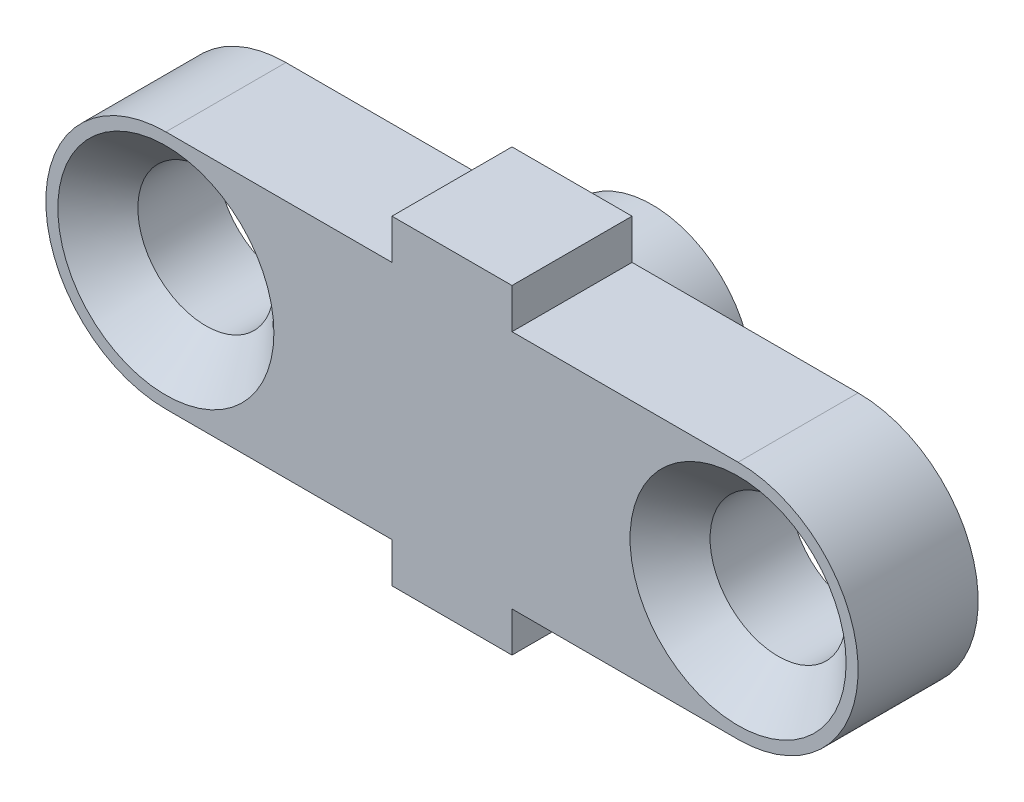
SolidWorks part; units mm, degrees
ref_plane "Top Plane" through (0, 0, 0) normal (0, 0, 1) x (1, 0, 0)
ref_plane "Right Plane" through (0, 0, 0) normal (0, 1, 0) x (1, 0, 0)
ref_plane "Front Plane" through (0, 0, 0) normal (1, 0, 0) x (0, 0, -1)
sketch "Sketch1" plane through (0, 0, 0) normal (0, 0, 1) x (1, 0, 0)
  line L0 (-7.15, 0) -> (7.15, 0) construction
  line L1 (-7.15, 3) -> (-1.5, 3)
  line L2 (-7.15, -3) -> (-1.5, -3)
  line L3 (-1.5, -3) -> (-1.5, -4)
  line L4 (-1.5, 4) -> (1.5, 4)
  line L5 (-1.5, 4) -> (-1.5, 3)
  line L6 (-1.5, -4) -> (1.5, -4)
  line L7 (1.5, 4) -> (1.5, 3)
  line L8 (1.5, -3) -> (1.5, -4)
  line L9 (0, 4) -> (0, -4) construction
  line L10 (1.5, 3) -> (7.15, 3)
  line L11 (-1.5, 3) -> (0, 3) construction
  line L12 (0, 3) -> (1.5, 3) construction
  line L13 (1.5, -3) -> (7.15, -3)
  line L14 (-1.5, -3) -> (0, -3) construction
  line L15 (0, -3) -> (1.5, -3) construction
  arc A0 (7.15, -3) -> (7.15, 3) centre (7.15, 0) ccw
  arc A1 (-7.15, 3) -> (-7.15, -3) centre (-7.15, 0) ccw
  circle A2 centre (-7.15, 0) radius 1.7
  circle A3 centre (7.15, 0) radius 1.7
  arc A4 (-7.15, -3) -> (-4.15, 0) centre (-7.15, 0) ccw construction
  arc A5 (-4.15, 0) -> (-7.15, 3) centre (-7.15, 0) ccw construction
  arc A6 (7.15, 3) -> (4.15, 0) centre (7.15, 0) ccw construction
  arc A7 (4.15, 0) -> (7.15, -3) centre (7.15, 0) ccw construction
  point P14 (0, 0)
  dimension "D1" = 14.3
  dimension "D2" = 6
  dimension "D3" = 3.4
  dimension "D4" = 3
  dimension "D5" = 8
extrude "Boss-Extrude1" add sketch "Sketch1" along normal blind 3
chamfer "Chamfer1" distance 1 angle 45 2 edges at (8.85, 0, 3) (-5.45, 0, 3)
sketch "Sketch2" plane through (0, 0, 0) normal (0, 0, -1) x (-1, 0, 0)
  circle A0 centre (0, 0) radius 2.5
  dimension "D1" = 5
extrude "Boss-Extrude2" add sketch "Sketch2" along normal blind 2
